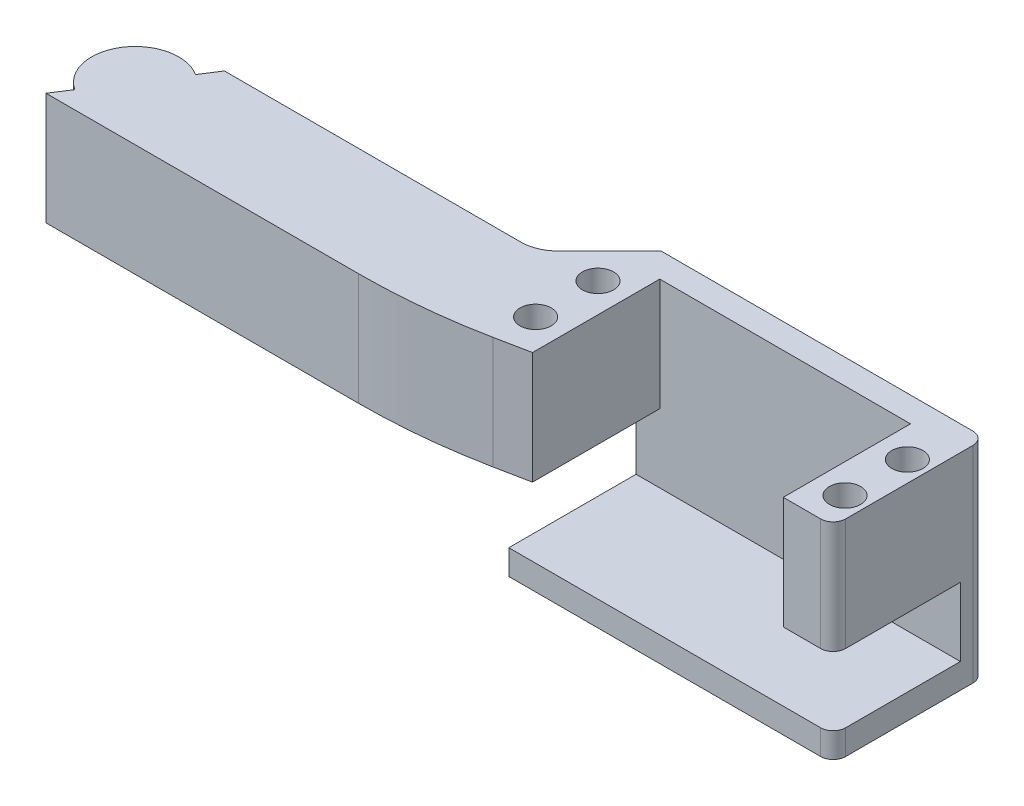
SolidWorks part; units mm, degrees
ref_plane "Front Plane" through (0, 0, 0) normal (0, 0, 1) x (1, 0, 0)
ref_plane "Top Plane" through (0, 0, 0) normal (0, 1, 0) x (1, 0, 0)
ref_plane "Right Plane" through (0, 0, 0) normal (1, 0, 0) x (0, 0, -1)
sketch "Sketch1" plane through (0, 0, 0) normal (0, 1, 0) x (1, 0, 0)
  line L0 (-40.2, 0) -> (-40.2, 20.4)
  line L1 (-40.2, 20.4) -> (0, 20.4)
  line L2 (0, 20.4) -> (0, 0)
  line L3 (0, 0) -> (8, 0)
  line L5 (8, 24.4) -> (-44, 24.4)
  line L11 (8, 24.4) -> (8, 0)
  line L14 (-44, 24.4) -> (-54, 14.4)
  line L15 (-54, 14.4) -> (-104, 14.4)
  line L16 (-40.2, 0) -> (-55.2, -3)
  line L17 (-55.2, -3) -> (-115.2, -3)
  line L18 (-115.2, -3) -> (-113.3887, -0.1861)
  line L19 (-105.8113, 11.5861) -> (-104, 14.4)
  line L20 (-115.2, -3) -> (-104, 14.4) construction
  arc A9 (-105.8113, 11.5861) -> (-113.3887, -0.1861) centre (-109.6, 5.7) ccw
  point P9 (0, 0)
  point P12 (-109.6, 5.7)
  dimension "D1" = 10
  dimension "D2" = 20.4
  dimension "D6" = 10
  dimension "D8" = 15
  dimension "D10" = 60
  dimension "D12" = 7
  dimension "D3" = 40.2
  dimension "D4" = 4
  dimension "D5" = 8
  dimension "D7" = 52
  dimension "D9" = 3
  dimension "D11" = 50
extrude "Boss-Extrude1" add sketch "Sketch1" along normal blind 18
sketch "Sketch2" plane through (0, 0, -24.4) normal (0, 0, -1) x (-1, 0, 0)
  line L1 (44, 18) -> (-8, 18)
  line L2 (44, 18) -> (44, -11)
  line L3 (44, -11) -> (-8, -11)
  line L4 (-8, 18) -> (-8, -11)
  line L6 (-8, 18) -> (-8, 0) construction
  line L9 (44, 18) -> (44, 0) construction
  line L10 (-8, 18) -> (44, 18) construction
  point P7 (0, 0)
  dimension "D1" = 29
extrude "Boss-Extrude2" add sketch "Sketch2" against normal up to surface (4 mm away) up to face at (-20.1, 9, -20.4)
sketch "Sketch3" plane through (0, -11, 0) normal (0, -1, 0) x (1, 0, 0)
  line L1 (8, -24.4) -> (-44, -24.4)
  line L2 (8, -24.4) -> (8, 0)
  line L3 (8, 0) -> (-44, 0)
  line L4 (-44, -24.4) -> (-44, 0)
  line L5 (-44, -20.4) -> (-44, -24.4) construction
  line L6 (0, 0) -> (8, 0) construction
extrude "Boss-Extrude3" add sketch "Sketch3" along normal blind 4
sketch "Sketch4" plane through (0, -15, 0) normal (0, -1, 0) x (1, 0, 0)
  circle A0 centre (-10.1, -10.2) radius 2.5
  circle A1 centre (-10.1, -10.2) radius 1.25 construction
  circle A2 centre (-10.1, -10.2) radius 1.25 construction
  point P2 (0, 0)
  dimension "D1" = 5
extrude "Boss-Extrude4" add sketch "Sketch4" along normal blind 5
sketch "Sketch5" plane through (0, 18, 0) normal (0, 1, 0) x (1, 0, 0)
  line L0 (-40.2, 20.4) -> (0, 20.4) construction
  line L1 (0, 20.4) -> (0, 0) construction
  line L2 (-20.1, 24.4) -> (-20.1, -2.2784) construction
  line L3 (8, 24.4) -> (-44, 24.4) construction
  circle A0 centre (4.7, 15.2) radius 2.5
  circle A1 centre (4.7, 5.2) radius 2.5
  circle A2 centre (-44.9, 5.2) radius 2.5
  circle A3 centre (-44.9, 15.2) radius 2.5
  dimension "D4" = 5
  dimension "D1" = 5.2
  dimension "D2" = 10
  dimension "D3" = 4.7
  dimension "D5" = 24.8
extrude "Cut-Extrude1" cut sketch "Sketch5" against normal up to surface (18 mm away) up to face at (4, 0, -10.2)
fillet "Fillet2" radius 6 1 edges at (-54, 9, -14.4)
fillet "Fillet4" radius 2 3 edges at (8, -13, 0) (8, 9, 0) (8, 1.5, -24.4)
fillet "Fillet5" radius 100 1 edges at (-55.2, 9, 3)
